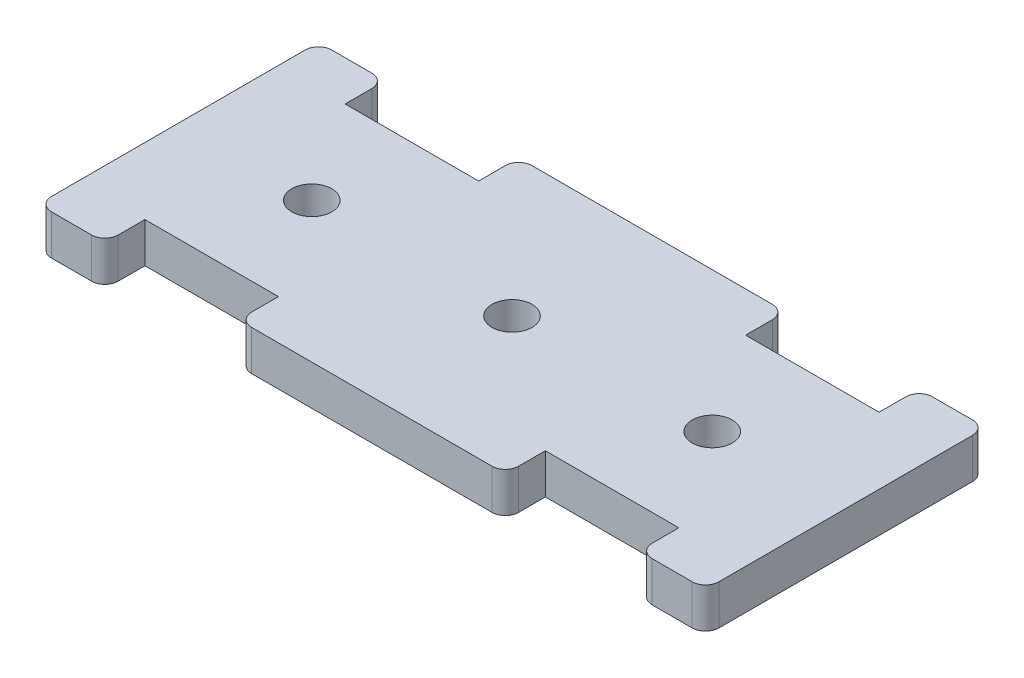
SolidWorks part; units mm, degrees
material "Thornel Mat VMA"
ref_plane "前视基准面" through (0, 0, 0) normal (0, 0, 1) x (1, 0, 0)
ref_plane "上视基准面" through (0, 0, 0) normal (0, 1, 0) x (1, 0, 0)
ref_plane "右视基准面" through (0, 0, 0) normal (1, 0, 0) x (0, 0, -1)
sketch "草图1" plane through (0, 0, 0) normal (0, 1, 0) x (1, 0, 0)
  line L0 (0, 0) -> (50, 0) construction
  line L1 (0, 10.5) -> (0, -10.5)
  line L2 (0, -10.5) -> (5, -10.5)
  line L3 (5, -10.5) -> (5, -7.5)
  line L4 (5, -7.5) -> (15, -7.5)
  line L5 (15, -7.5) -> (15, -10.5)
  line L6 (15, -10.5) -> (35, -10.5)
  line L7 (35, 10.5) -> (35, 7.5)
  line L8 (15, 10.5) -> (35, 10.5)
  line L9 (15, 7.5) -> (15, 10.5)
  line L10 (5, 7.5) -> (15, 7.5)
  line L11 (5, 10.5) -> (5, 7.5)
  line L12 (0, 10.5) -> (5, 10.5)
  line L14 (35, -10.5) -> (35, -7.5)
  line L15 (35, -7.5) -> (45, -7.5)
  line L16 (45, -7.5) -> (45, -10.5)
  line L17 (45, -10.5) -> (50, -10.5)
  line L18 (50, -10.5) -> (50, 10.5)
  line L19 (45, 10.5) -> (50, 10.5)
  line L20 (45, 7.5) -> (45, 10.5)
  line L21 (35, 7.5) -> (45, 7.5)
  circle A0 centre (10, 0) radius 1.5
  circle A1 centre (40, 0) radius 1.5
  circle A2 centre (25, 0) radius 1.5
  point P25 (10, 7.5)
  point P26 (40, 7.5)
  dimension "D7" = 3
  dimension "D1" = 5
  dimension "D2" = 10
  dimension "D3" = 20
  dimension "D4" = 5
  dimension "D5" = 3
  dimension "D6" = 15
extrude "凸台-拉伸1" add sketch "草图1" along normal blind 3
fillet "圆角1" radius 1 12 edges at (15, 1.5, 10.5) (35, 1.5, 10.5) (45, 1.5, 10.5) (50, 1.5, 10.5) (45, 1.5, -10.5) (50, 1.5, -10.5) (35, 1.5, -10.5) (15, 1.5, -10.5) (0, 1.5, -10.5) (5, 1.5, -10.5) (0, 1.5, 10.5) (5, 1.5, 10.5)
